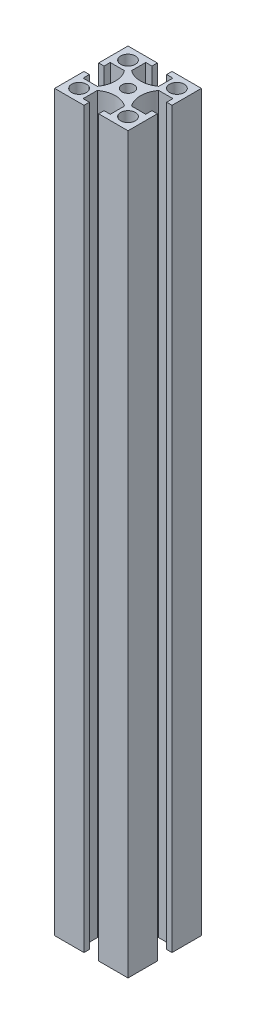
SolidWorks part; units mm, degrees
material "1060 Alloy"
ref_plane "Front Plane" through (0, 0, 0) normal (0, 0, 1) x (1, 0, 0)
ref_plane "Top Plane" through (0, 0, 0) normal (0, 1, 0) x (1, 0, 0)
ref_plane "Right Plane" through (0, 0, 0) normal (1, 0, 0) x (0, 0, -1)
sketch "Sketch1" plane through (0, 0, 0) normal (0, 1, 0) x (1, 0, 0)
  line L0 (-3, -15) -> (-3, -12.8)
  line L1 (15, 15) -> (3, 15)
  line L2 (15, 15) -> (15, 3)
  line L3 (15, -15) -> (3, -15)
  line L4 (-15, 15) -> (-15, 3)
  line L5 (15, 15) -> (-15, -15) construction
  line L6 (15, -15) -> (-15, 15) construction
  line L7 (-3, -12.8) -> (-5.55, -12.8)
  line L8 (-5.55, -12.8) -> (-5.55, -7)
  line L9 (3, -15) -> (3, -12.8)
  line L10 (3, -12.8) -> (5.55, -12.8)
  line L11 (5.55, -12.8) -> (5.55, -7)
  line L12 (0, -5.16) -> (0, -15) construction
  line L13 (-12.8, 5.55) -> (-7, 5.55)
  line L14 (-12.8, -5.55) -> (-7, -5.55)
  line L15 (-12.8, -3) -> (-12.8, -5.55)
  line L16 (-15, -3) -> (-12.8, -3)
  line L17 (-5.16, 0) -> (-15, 0) construction
  line L18 (-15, 3) -> (-12.8, 3)
  line L19 (-12.8, 3) -> (-12.8, 5.55)
  line L20 (5.55, 12.8) -> (5.55, 7)
  line L21 (-5.55, 12.8) -> (-5.55, 7)
  line L22 (-3, 12.8) -> (-5.55, 12.8)
  line L23 (-3, 15) -> (-3, 12.8)
  line L24 (0, 5.16) -> (0, 15) construction
  line L25 (3, 15) -> (3, 12.8)
  line L26 (3, 12.8) -> (5.55, 12.8)
  line L27 (12.8, -5.55) -> (7, -5.55)
  line L28 (12.8, 5.55) -> (7, 5.55)
  line L29 (12.8, 3) -> (12.8, 5.55)
  line L30 (15, 3) -> (12.8, 3)
  line L31 (5.16, 0) -> (15, 0) construction
  line L32 (15, -3) -> (12.8, -3)
  line L33 (12.8, -3) -> (12.8, -5.55)
  line L34 (-3, -15) -> (-15, -15)
  line L35 (15, -3) -> (15, -15)
  line L36 (-3, 15) -> (-15, 15)
  line L37 (-15, -3) -> (-15, -15)
  arc A0 (-5.55, -7) -> (5.55, -7) centre (0, -14.4502) cw
  arc A1 (-7, 5.55) -> (-7, -5.55) centre (-14.4502, 0) cw
  arc A2 (5.55, 7) -> (-5.55, 7) centre (0, 14.4502) cw
  arc A3 (7, -5.55) -> (7, 5.55) centre (14.4502, 0) cw
  circle A4 centre (-10, 10) radius 3
  circle A5 centre (10, 10) radius 3
  circle A6 centre (-10, -10) radius 3
  circle A7 centre (10, -10) radius 3
  circle A8 centre (0, 0) radius 2.5
  point P0 (0, 0)
  point P53 (0, 0)
  dimension "D12" = 6
  dimension "D25" = 5
  dimension "D26" = 6
  dimension "D1" = 1.84
  dimension "D2" = 6
  dimension "D3" = 11.1
  dimension "D4" = 15
  dimension "D5" = 30
  dimension "D6" = 30
  dimension "D7" = 9.84
  dimension "D8" = 2.2
  dimension "D10" = 15
  dimension "D11" = 15
  dimension "D9" = 15
  dimension "D13" = 6
  dimension "D14" = 6
  dimension "D15" = 2.2
  dimension "D16" = 2.2
  dimension "D17" = 2.2
  dimension "D18" = 11.1
  dimension "D19" = 5.55
  dimension "D20" = 1.84
  dimension "D21" = 1.84
  dimension "D22" = 2.2
  dimension "D23" = 9.84
  dimension "D24" = 9.84
  dimension "D27" = 10
  dimension "D28" = 10
  dimension "D29" = 10
  dimension "D30" = 10
extrude "Boss-Extrude1" add sketch "Sketch1" along normal blind 300
